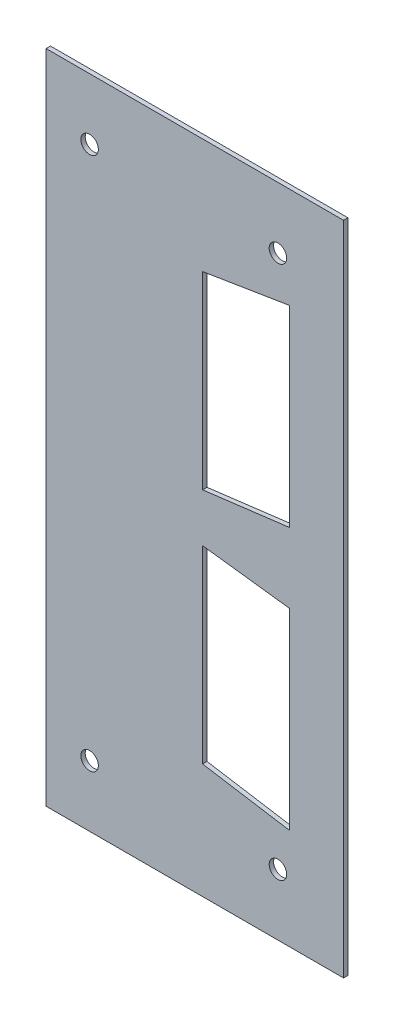
SolidWorks part; units mm, degrees
material "AISI 1010 Steel, hot rolled bar"
ref_plane "Front Plane" through (0, 0, 0) normal (0, 0, 1) x (1, 0, 0)
ref_plane "Top Plane" through (0, 0, 0) normal (0, 1, 0) x (1, 0, 0)
ref_plane "Right Plane" through (0, 0, 0) normal (1, 0, 0) x (0, 0, -1)
sketch "Sketch1" plane through (0, 0, 0) normal (0, 0, 1) x (1, 0, 0)
  line L1 (0, 0) -> (68, 0)
  line L2 (0, 0) -> (0, 150)
  line L3 (0, 150) -> (68, 150)
  line L4 (68, 0) -> (68, 150)
  dimension "D1" = 68
  dimension "D2" = 150
extrude "Boss-Extrude1" add sketch "Sketch1" along normal blind 1
sketch "Sketch2" plane through (0, 0, 1) normal (0, 0, 1) x (1, 0, 0)
  line L0 (0, 75) -> (68, 75) construction
  line L1 (0, 150) -> (0, 0) construction
  line L2 (68, 0) -> (68, 150) construction
  line L3 (0, 0) -> (68, 0) construction
  circle A0 centre (9.95, 14) radius 2
  circle A1 centre (53, 14) radius 2
  circle A2 centre (53, 136) radius 2
  circle A3 centre (9.95, 136) radius 2
  dimension "D1" = 4
  dimension "D2" = 14
  dimension "D3" = 9.95
  dimension "D5" = 14
  dimension "D4" = 15
extrude "Cut-Extrude1" cut sketch "Sketch2" against normal blind 1
sketch "Sketch3" plane through (0, 0, 0) normal (0, 0, -1) x (-1, 0, 0)
  line L0 (-35.78, 80.53) -> (-35.78, 123.74)
  line L1 (-35.78, 123.74) -> (-55.64, 126.96)
  line L2 (-55.64, 126.96) -> (-55.64, 83.01)
  line L3 (-55.64, 83.01) -> (-35.78, 80.53)
  line L4 (-68, 150) -> (0, 150) construction
  line L6 (0, 150) -> (0, 0) construction
  line L7 (-68, 0) -> (-68, 150) construction
  line L8 (-68, 150) -> (0, 150) construction
  line L9 (0, 75) -> (-68, 75) construction
  line L10 (-55.64, 66.99) -> (-35.78, 69.47)
  line L11 (-55.64, 23.04) -> (-55.64, 66.99)
  line L12 (-35.78, 26.26) -> (-55.64, 23.04)
  line L13 (-35.78, 69.47) -> (-35.78, 26.26)
  dimension "D1" = 26.26
  dimension "D2" = 35.78
  dimension "D3" = 23.04
  dimension "D4" = 12.36
  dimension "D5" = 66.99
  dimension "D6" = 69.47
extrude "Cut-Extrude2" cut sketch "Sketch3" against normal blind 20
